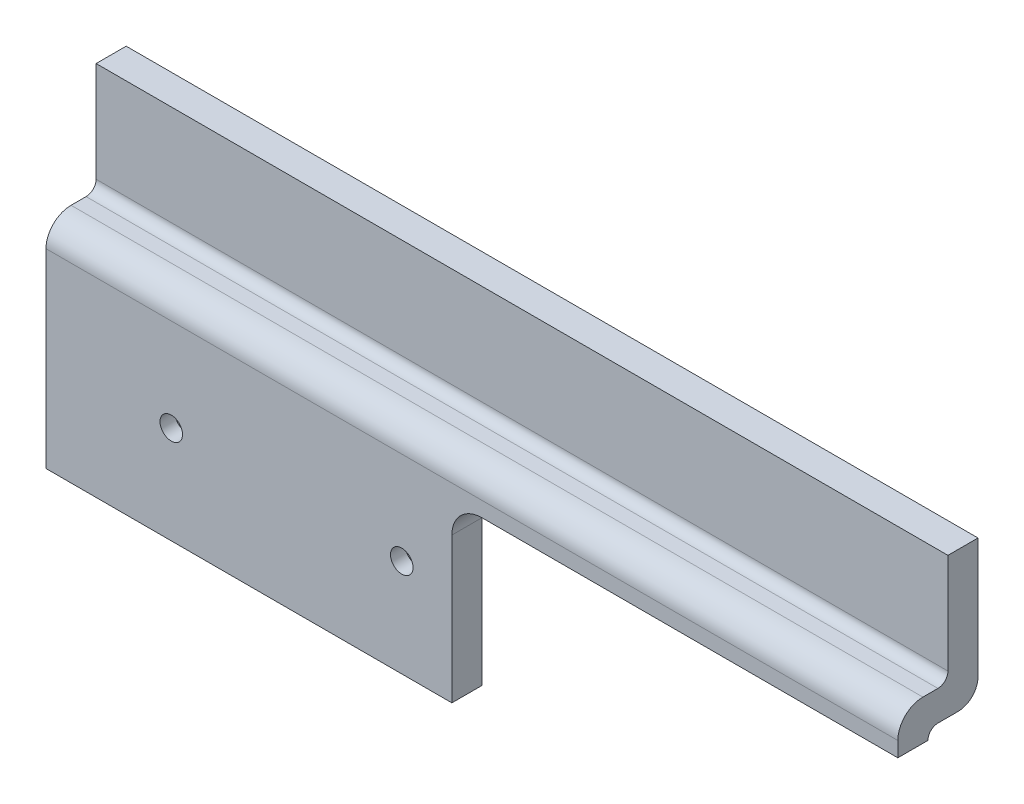
SolidWorks part; units mm, degrees
material "ABS"
ref_plane "Piano frontale" through (0, 0, 0) normal (0, 0, 1) x (1, 0, 0)
ref_plane "Piano superiore" through (0, 0, 0) normal (0, 1, 0) x (1, 0, 0)
ref_plane "Piano destro" through (0, 0, 0) normal (1, 0, 0) x (0, 0, -1)
sketch "Schizzo1" plane through (0, 0, 0) normal (1, 0, 0) x (0, 0, -1)
  line L0 (0, 0) -> (6, 0)
  line L1 (6, 0) -> (6, 35)
  line L2 (8, 37) -> (12, 37)
  line L3 (16, 41) -> (16, 65)
  line L4 (16, 65) -> (10, 65)
  line L5 (10, 65) -> (10, 45)
  line L6 (8, 43) -> (5, 43)
  line L7 (0, 38) -> (0, 0)
  arc A0 (5, 43) -> (0, 38) centre (5, 38) ccw
  arc A1 (10, 45) -> (8, 43) centre (8, 45) cw
  arc A2 (8, 37) -> (6, 35) centre (8, 35) ccw
  arc A3 (12, 37) -> (16, 41) centre (12, 41) ccw
  dimension "D7" = 5
  dimension "D8" = 2
  dimension "D9" = 4
  dimension "D1" = 37
  dimension "D2" = 43
  dimension "D3" = 6
  dimension "D4" = 16
  dimension "D5" = 6
  dimension "D6" = 28
extrude "Estrusione-Estrusione1" add sketch "Schizzo1" along normal blind 170
sketch "Schizzo2" plane through (0, 0, -6) normal (0, 0, -1) x (-1, 0, 0)
  line L0 (-71, 19.5) -> (-25, 19.5) construction
  line L2 (0, 0) -> (0, 35) construction
  point P0 (-25, 19.5)
  point P2 (-71, 19.5)
  dimension "D1" = 46
  dimension "D2" = 25
  dimension "D3" = 23.5
hole_wizard "Foro lamato per Bullone M5 a testa esagonale-1" positions "Schizzo2" profile "Schizzo3" counterbore size "M5" standard "ISO"
sketch "Schizzo3" plane through (25, 19.5, -6) normal (1, 0, 0) x (0, 1, 0)
  line L0 (0, 0) -> (0, 31.3519)
  line L1 (0, 31.3519) -> (2.25, 30)
  line L2 (2.25, 30) -> (2.25, 3)
  line L3 (2.25, 3) -> (5, 3)
  line L4 (5, 3) -> (5, 0)
  line L5 (5, 0) -> (0, 0)
  line L10 (0, 31.3519) -> (-2.25, 30) construction
  line L11 (0, -6.35) -> (0, 107.95) construction
  dimension "Hole Dia." = 4.5
  dimension "Hole Depth" = 30
  dimension "C'Bore Dia." = 10
  dimension "C'Bore Depth" = 3
  dimension "Drill Angle" = 118
sketch "Schizzo4" plane through (0, 0, -6) normal (0, 0, -1) x (-1, 0, 0)
  line L1 (-170, 0) -> (-81, 0)
  line L2 (-170, 0) -> (-170, 35)
  line L3 (-170, 35) -> (-81, 35)
  line L4 (-81, 0) -> (-81, 35)
  circle A0 centre (-71, 19.5) radius 2.25 construction
  dimension "D1" = 10
  dimension "D2" = 35
extrude "Taglio-Estrusione1" cut sketch "Schizzo4" against normal blind 170
fillet "Raccordo1" radius 6 1 edges at (81, 35, -3)
